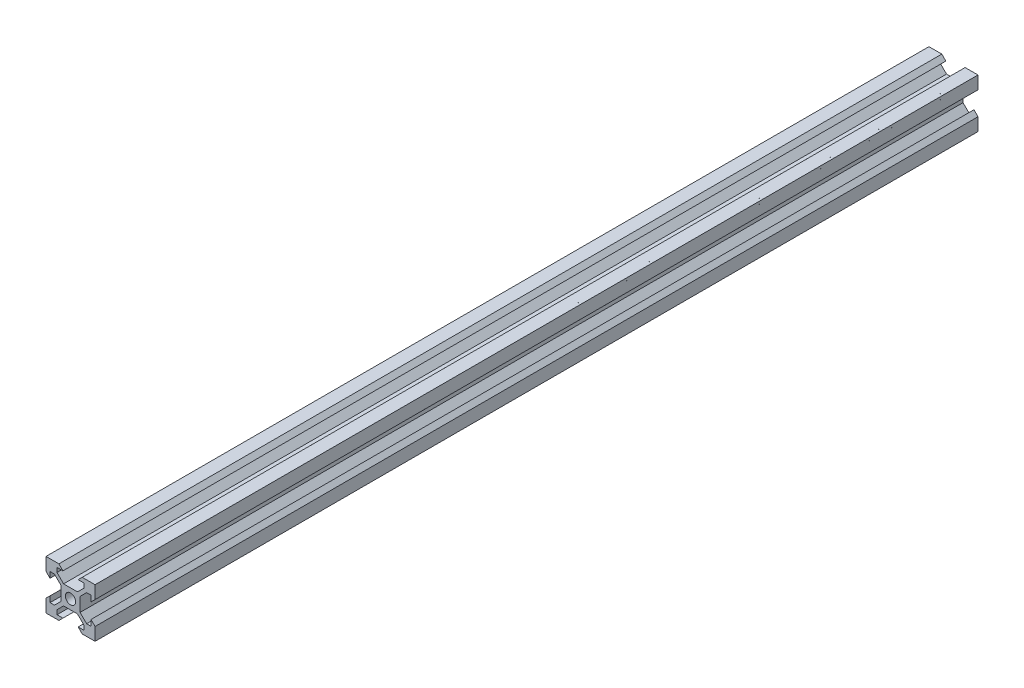
SolidWorks part; units mm, degrees
material "6061-T6 (SS)"
ref_plane "Front Plane" through (0, 0, 0) normal (0, 0, 1) x (1, 0, 0)
ref_plane "Top Plane" through (0, 0, 0) normal (0, 1, 0) x (1, 0, 0)
ref_plane "Right Plane" through (0, 0, 0) normal (1, 0, 0) x (0, 0, -1)
sketch "Sketch1" plane through (0, 0, 0) normal (0, 0, 1) x (1, 0, 0)
  line L0 (2.8343, 3.894) -> (5.5, 6.5588)
  line L1 (2.8343, -3.894) -> (-2.8343, -3.894)
  line L2 (3.8948, -2.8332) -> (3.8948, 2.8332)
  line L3 (2.8343, 3.894) -> (-2.8343, 3.894)
  line L4 (-3.8948, -2.8332) -> (-3.8948, 2.8332)
  line L5 (3.8994, -3.9006) -> (-3.8994, 3.9006) construction
  line L6 (3.9006, 3.8994) -> (-3.9006, -3.8994) construction
  line L7 (10, 4.747) -> (10, 9.9986)
  line L8 (5.5, 6.5588) -> (5.5, 8.3491)
  line L9 (5.5, 8.3491) -> (3.1, 8.3491)
  line L10 (3.1, 8.3491) -> (4.75, 9.9986)
  line L11 (4.75, 9.9986) -> (10, 9.9986)
  line L12 (8.35, 3.0975) -> (10, 4.747)
  line L13 (8.3507, 5.4975) -> (8.35, 3.0975)
  line L14 (6.5605, 5.498) -> (8.3507, 5.4975)
  line L15 (3.8948, 2.8332) -> (6.5605, 5.498)
  line L16 (0, -55) -> (0, 55) construction
  line L17 (-3.8948, 2.8332) -> (-6.5605, 5.498)
  line L18 (-6.5605, 5.498) -> (-8.3507, 5.4975)
  line L19 (-8.3507, 5.4975) -> (-8.35, 3.0975)
  line L20 (-8.35, 3.0975) -> (-10, 4.747)
  line L21 (-4.75, 9.9986) -> (-10, 9.9986)
  line L22 (-3.1, 8.3491) -> (-4.75, 9.9986)
  line L23 (-5.5, 8.3491) -> (-3.1, 8.3491)
  line L24 (-5.5, 6.5588) -> (-5.5, 8.3491)
  line L25 (-10, 4.747) -> (-10, 9.9986)
  line L26 (-2.8343, 3.894) -> (-5.5, 6.5588)
  line L27 (55, 0) -> (-55, 0) construction
  line L28 (3.8948, -2.8332) -> (6.5605, -5.498)
  line L29 (2.8343, -3.894) -> (5.5, -6.5588)
  line L30 (-3.8948, -2.8332) -> (-6.5605, -5.498)
  line L31 (-2.8343, -3.894) -> (-5.5, -6.5588)
  line L32 (-8.3507, -5.4975) -> (-8.35, -3.0975)
  line L33 (-8.35, -3.0975) -> (-10, -4.747)
  line L34 (8.3507, -5.4975) -> (8.35, -3.0975)
  line L35 (8.35, -3.0975) -> (10, -4.747)
  line L36 (-10, -4.747) -> (-10, -9.9986)
  line L37 (-5.5, -6.5588) -> (-5.5, -8.3491)
  line L38 (-5.5, -8.3491) -> (-3.1, -8.3491)
  line L39 (-3.1, -8.3491) -> (-4.75, -9.9986)
  line L40 (-4.75, -9.9986) -> (-10, -9.9986)
  line L41 (-6.5605, -5.498) -> (-8.3507, -5.4975)
  line L42 (6.5605, -5.498) -> (8.3507, -5.4975)
  line L43 (4.75, -9.9986) -> (10, -9.9986)
  line L44 (3.1, -8.3491) -> (4.75, -9.9986)
  line L45 (5.5, -8.3491) -> (3.1, -8.3491)
  line L46 (5.5, -6.5588) -> (5.5, -8.3491)
  line L47 (10, -4.747) -> (10, -9.9986)
  circle A0 centre (0, 0) radius 2.1
  point P0 (0, 0)
  dimension "D6" = 4.2
  dimension "D1" = 7.8
  dimension "D2" = 20
  dimension "D3" = 11
  dimension "D4" = 9.5
  dimension "D5" = 6.2
  dimension "D7" = 1.5
extrude "Boss-Extrude1" add sketch "Sketch1" along normal blind 360
